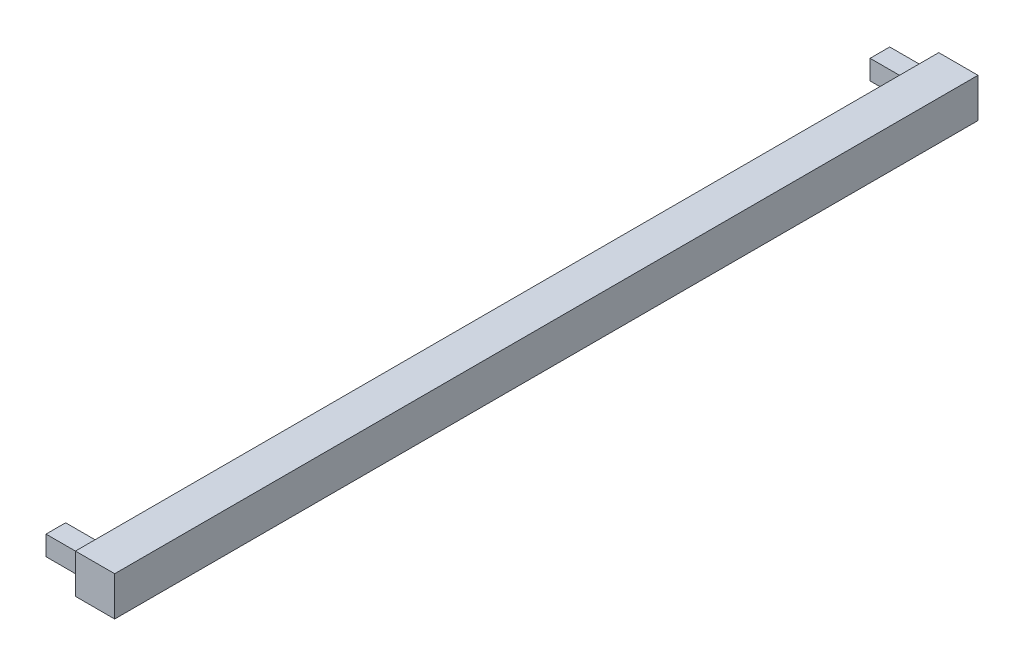
SolidWorks part; units mm, degrees
ref_plane "Front Plane" through (0, 0, 0) normal (0, 0, 1) x (1, 0, 0)
ref_plane "Top Plane" through (0, 0, 0) normal (0, 1, 0) x (1, 0, 0)
ref_plane "Right Plane" through (0, 0, 0) normal (1, 0, 0) x (0, 0, -1)
sketch "Sketch1" plane through (0, 0, 0) normal (0, 0, 1) x (1, 0, 0)
  line L1 (0, 0) -> (5, 0)
  line L2 (0, 0) -> (0, 5)
  line L3 (0, 5) -> (5, 5)
  line L4 (5, 0) -> (5, 5)
  dimension "D1" = 5
  dimension "D2" = 5
extrude "Boss-Extrude1" add sketch "Sketch1" along normal blind 110
sketch "Sketch2" plane through (0, 0, 0) normal (-1, 0, 0) x (0, 0, 1)
  line L0 (0, 5) -> (0, 0) construction
  line L1 (1.25, 1.25) -> (3.75, 1.25)
  line L2 (1.25, 1.25) -> (1.25, 3.75)
  line L3 (1.25, 3.75) -> (3.75, 3.75)
  line L4 (3.75, 1.25) -> (3.75, 3.75)
  line L5 (110, 5) -> (0, 5) construction
  line L6 (110, 5) -> (110, 0) construction
  line L7 (108.75, 3.75) -> (106.25, 3.75)
  line L8 (108.75, 3.75) -> (108.75, 1.25)
  line L9 (108.75, 1.25) -> (106.25, 1.25)
  line L10 (106.25, 3.75) -> (106.25, 1.25)
  dimension "D1" = 2.5
  dimension "D2" = 2.5
  dimension "D3" = 1.25
  dimension "D4" = 1.25
  dimension "D5" = 2.5
  dimension "D6" = 2.5
  dimension "D7" = 1.25
  dimension "D8" = 1.25
extrude "Boss-Extrude2" add sketch "Sketch2" along normal blind 5
